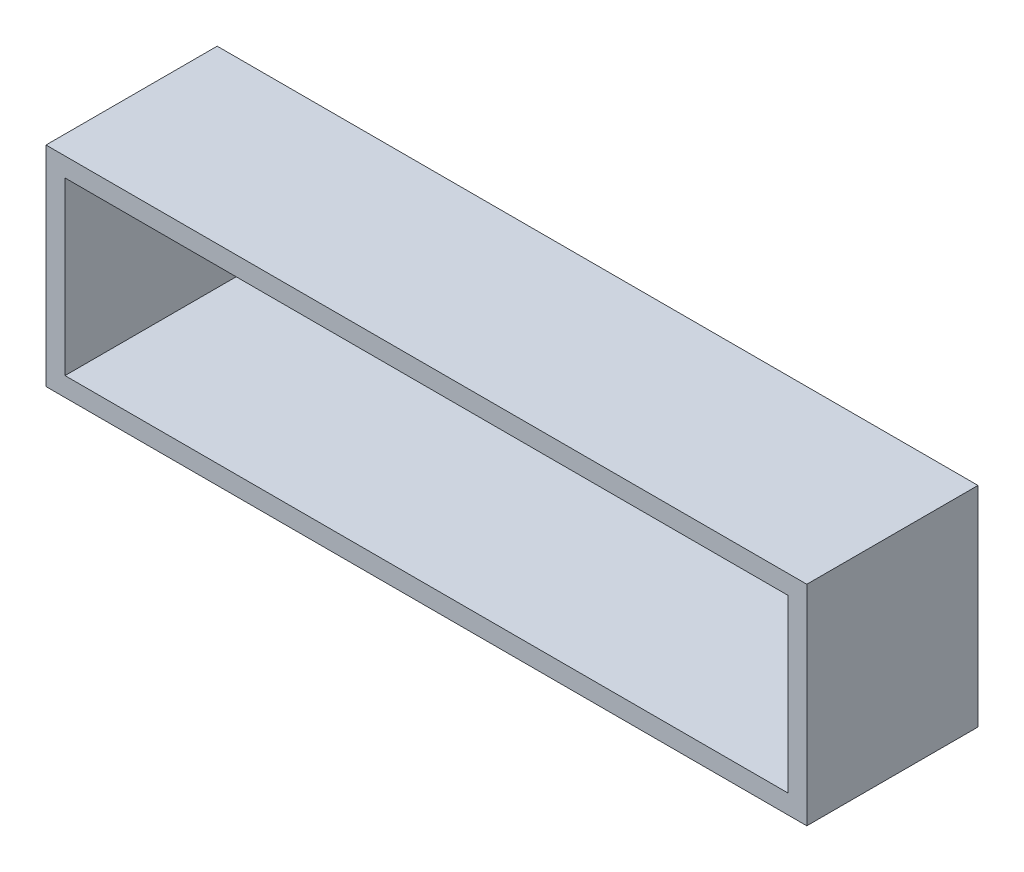
SolidWorks part; units mm, degrees
ref_plane "Front Plane" through (0, 0, 0) normal (0, 0, 1) x (1, 0, 0)
ref_plane "Top Plane" through (0, 0, 0) normal (0, 1, 0) x (1, 0, 0)
ref_plane "Right Plane" through (0, 0, 0) normal (1, 0, 0) x (0, 0, -1)
sketch "Sketch1" plane through (0, 0, 0) normal (0, 1, 0) x (1, 0, 0)
  line L1 (0, 0) -> (200, 0)
  line L2 (0, 0) -> (0, 45)
  line L3 (0, 45) -> (200, 45)
  line L4 (200, 0) -> (200, 45)
  dimension "D1" = 200
  dimension "D2" = 45
extrude "Boss-Extrude1" add sketch "Sketch1" along normal blind 55
sketch "Sketch2" plane through (0, 0, 0) normal (0, 0, 1) x (1, 0, 0)
  line L0 (100, 55) -> (100, -11.2335) construction
  line L1 (0, 55) -> (200, 55) construction
  line L2 (0, 27.5) -> (200, 27.5) construction
  line L3 (0, 55) -> (0, 0) construction
  line L4 (200, 55) -> (200, 0) construction
  line L6 (5, 5) -> (195, 5)
  line L7 (5, 5) -> (5, 50)
  line L8 (5, 50) -> (195, 50)
  line L9 (195, 5) -> (195, 50)
  line L10 (5, 5) -> (195, 50) construction
  line L11 (5, 50) -> (195, 5) construction
  point P10 (100, 27.5)
  dimension "D1" = 5
  dimension "D2" = 5
extrude "Cut-Extrude1" cut sketch "Sketch2" against normal through all both and the other way through all
sketch "body sketch" plane through (0, 0, 0) normal (-1, 0, 0) x (0, 0, 1)
  line L0 (-32.3141, 63.1814) -> (-32.3141, 54.9899) construction
  line L1 (-34.2928, 62.8873) -> (-30.3354, 62.8873)
  line L2 (-29.4378, 62.5332) -> (-25.5834, 58.6787)
  line L3 (-25.5834, 58.6787) -> (-25.5834, 58.2179)
  line L4 (-26.0442, 57.7571) -> (-28.5939, 57.7571)
  line L5 (-29.4378, 56.9132) -> (-29.4378, 55.362)
  line L6 (-35.1904, 56.9132) -> (-35.1904, 55.362)
  line L7 (-38.584, 57.7571) -> (-36.0343, 57.7571)
  line L8 (-39.0448, 58.6787) -> (-39.0448, 58.2179)
  line L9 (-35.1904, 62.5332) -> (-39.0448, 58.6787)
  line L10 (-35.4824, 55) -> (-45, 55)
  line L11 (-45, 55) -> (-45, 0)
  line L12 (-45, 0) -> (0, 0)
  line L13 (0, 0) -> (0, 55)
  line L14 (0, 55) -> (-29.1458, 55)
  arc A0 (-28.5939, 57.7571) -> (-29.4378, 56.9132) centre (-28.5704, 56.8897) ccw
  arc A1 (-26.0442, 57.7571) -> (-25.5834, 58.2179) centre (-26.1789, 58.3526) ccw
  arc A2 (-29.4378, 55.362) -> (-29.1458, 55) centre (-29.0587, 55.3691) ccw
  arc A3 (-30.3354, 62.8873) -> (-29.4378, 62.5332) centre (-30.6959, 60.659) cw
  arc A4 (-35.1904, 55.362) -> (-35.4824, 55) centre (-35.5695, 55.3691) cw
  arc A5 (-36.0343, 57.7571) -> (-35.1904, 56.9132) centre (-36.0578, 56.8897) cw
  arc A6 (-38.584, 57.7571) -> (-39.0448, 58.2179) centre (-38.4493, 58.3526) cw
  arc A7 (-34.2928, 62.8873) -> (-35.1904, 62.5332) centre (-33.9323, 60.659) ccw
  point P5 (-32.3141, 62.8873)
  point P33 (-32.3141, 62.8873)
